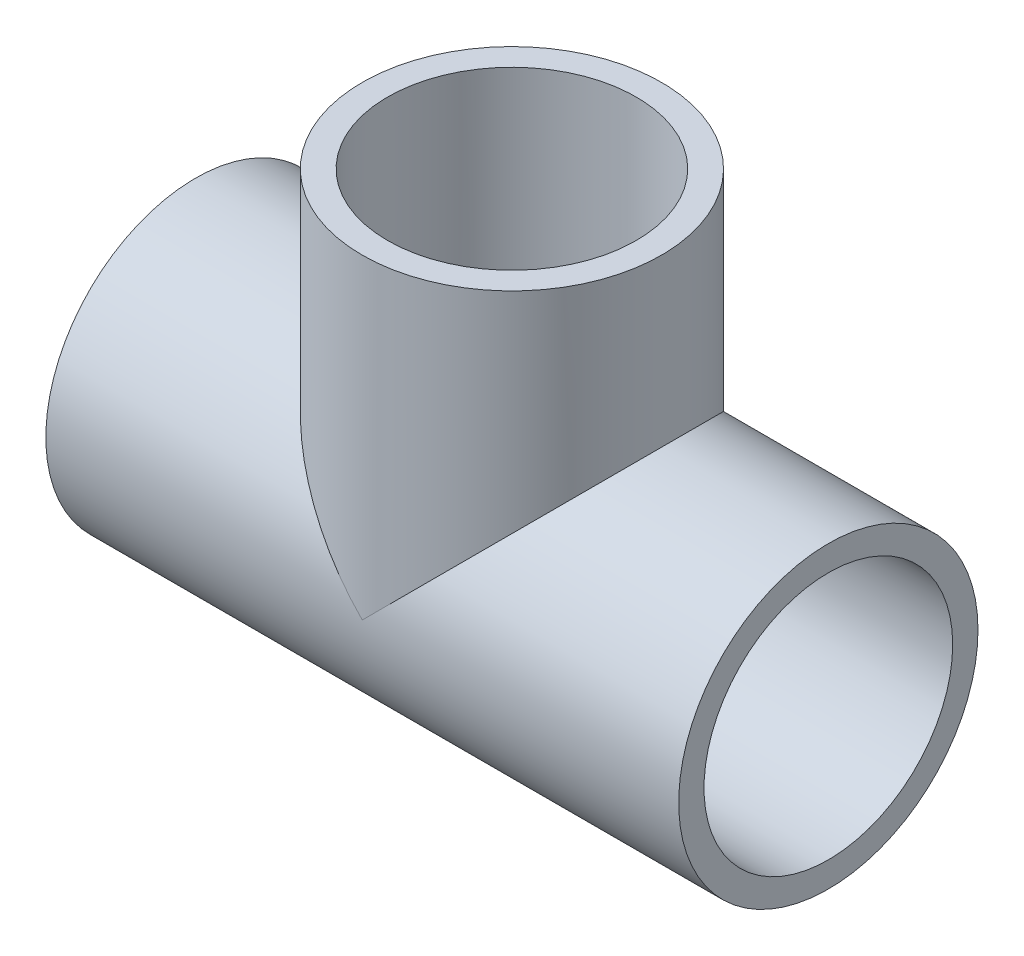
SolidWorks part; units mm, degrees
material "PVC Rígido"
ref_plane "Alzado" through (0, 0, 0) normal (0, 0, 1) x (1, 0, 0)
ref_plane "Planta" through (0, 0, 0) normal (0, 1, 0) x (1, 0, 0)
ref_plane "Vista lateral" through (0, 0, 0) normal (1, 0, 0) x (0, 0, -1)
sketch "Croquis1" plane through (0, 0, 0) normal (1, 0, 0) x (0, 0, -1)
  circle A0 centre (0, 0) radius 16.7
  circle A1 centre (0, 0) radius 20.1
  dimension "D1" = 33.4
  dimension "D2" = 40.2
extrude "Saliente-Extruir1" add sketch "Croquis1" along normal blind 85
sketch "Croquis2" plane through (0, 0, 0) normal (0, 1, 0) x (1, 0, 0)
  line L0 (42.5, 20.1) -> (42.5, -20.1) construction
  line L1 (85, 20.1) -> (0, 20.1) construction
  line L2 (0, -20.1) -> (85, -20.1) construction
  circle A0 centre (42.5, 0) radius 20.1
  circle A1 centre (42.5, 0) radius 16.7
  dimension "D1" = 33.4
extrude "Saliente-Extruir2" add sketch "Croquis2" along normal blind 42.44
sketch "Croquis3" plane through (0, 0, 0) normal (-1, 0, 0) x (0, 0, 1)
  circle A0 centre (0, 0) radius 16.7
extrude "Cortar-Extruir1" cut sketch "Croquis3" against normal blind 84.4974
sketch "Croquis5" plane through (0, 42.44, 0) normal (0, 1, 0) x (1, 0, 0)
  line L0 (25.8, 0) -> (59.2, 0) construction
  circle A0 centre (42.5, 0) radius 16.7 construction
  circle A1 centre (42.5, 0) radius 16.7 construction
  circle A2 centre (42.5, 0) radius 16.7
extrude "Cortar-Extruir2" cut sketch "Croquis5" against normal blind 42.4974
